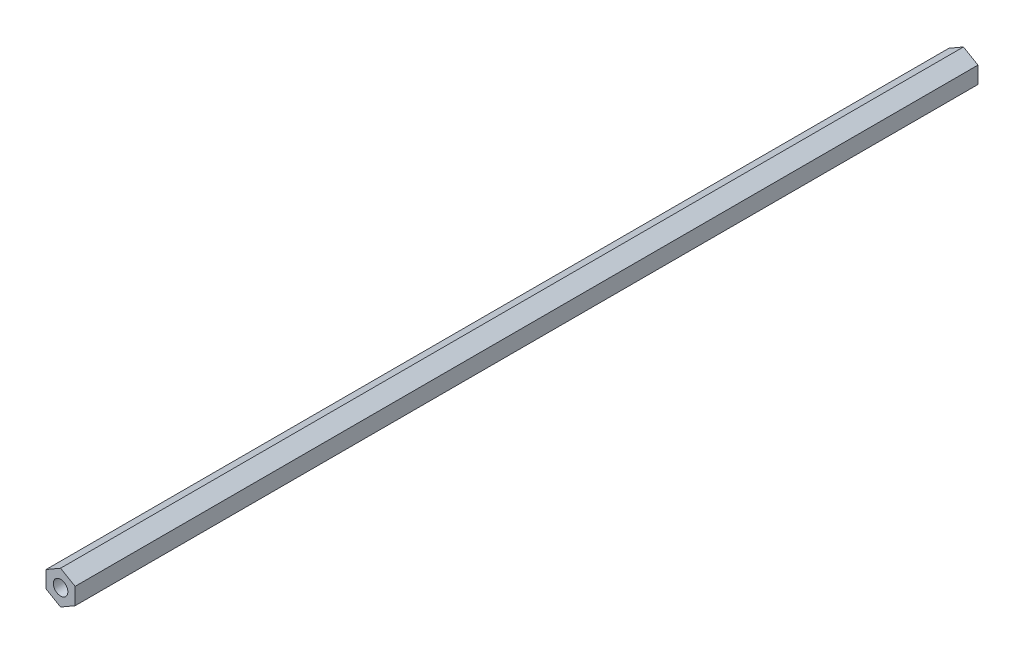
SolidWorks part; units mm, degrees
material "AISI 1020 Steel, Cold Rolled"
ref_plane "Front Plane" through (0, 0, 0) normal (0, 0, 1) x (1, 0, 0)
ref_plane "Top Plane" through (0, 0, 0) normal (0, 1, 0) x (1, 0, 0)
ref_plane "Right Plane" through (0, 0, 0) normal (1, 0, 0) x (0, 0, -1)
sketch "Sketch1" plane through (0, 0, 0) normal (0, 0, 1) x (1, 0, 0)
  line L1 (0, 7.3323) -> (-6.35, 3.6662) construction
  line L2 (-6.35, 3.6662) -> (-6.35, -3.6662) construction
  line L3 (-6.35, -3.6662) -> (0, -7.3323) construction
  line L4 (0, -7.3323) -> (6.35, -3.6662) construction
  line L5 (6.35, -3.6662) -> (6.35, 3.6662) construction
  line L6 (6.35, 3.6662) -> (0, 7.3323) construction
  circle A2 centre (0, 0) radius 6.35 construction
  dimension "Width" = 12.7
sketch "Sketch2" plane through (0, 0, 0) normal (1, 0, 0) x (0, 0, -1)
  line L0 (-196.85, 7.3323) -> (196.85, 7.3323) construction
  point P2 (0, 7.3323)
  point P3 (165.1, 7.3323)
  point P4 (-165.1, 7.3323)
  dimension "Length" = 393.7
  dimension "D2" = 31.75
  dimension "D1" = 31.75
sketch "Sketch3" plane through (0, 0, 0) normal (0, 0, 1) x (1, 0, 0)
  line L0 (-6.35, -3.6662) -> (0, -7.3323) construction
  line L1 (0, -7.3323) -> (6.35, -3.6662) construction
  line L2 (6.35, -3.6662) -> (6.35, 3.6662) construction
  line L3 (6.35, 3.6662) -> (0, 7.3323) construction
  line L4 (0, 7.3323) -> (-6.35, 3.6662) construction
  line L5 (-6.35, 3.6662) -> (-6.35, -3.6662) construction
  line L6 (-6.35, -3.6662) -> (0, -7.3323)
  line L7 (0, -7.3323) -> (6.35, -3.6662)
  line L8 (6.35, -3.6662) -> (6.35, 3.6662)
  line L9 (6.35, 3.6662) -> (0, 7.3323)
  line L10 (0, 7.3323) -> (-6.35, 3.6662)
  line L11 (-6.35, 3.6662) -> (-6.35, -3.6662)
extrude "Boss-Extrude2" add sketch "Sketch3" along normal up to vertex (196.85 mm away) and the other way up to vertex (196.85 mm away) up to point (0, 7.3323, 196.85) other way up to point (0, 7.3323, -196.85)
sketch "Sketch4" plane through (0, 0, 196.85) normal (0, 0, 1) x (1, 0, 0)
  point P0 (0, 0)
hole_wizard "1/4 (0.25) Diameter Hole1" positions "Sketch5" profile "Sketch6" hole size "1/4" standard "ANSI Inch"
sketch "Sketch5" plane through (0, 0, 196.85) normal (0, 0, 1) x (1, 0, 0)
  point P0 (0, 0)
sketch "Sketch6" plane through (0, 0, 196.85) normal (1, 0, 0) x (0, -1, 0)
  line L0 (0, 0) -> (0, 27.3077)
  line L1 (0, 27.3077) -> (3.175, 25.4)
  line L2 (3.175, 25.4) -> (3.175, 0)
  line L5 (3.175, 0) -> (0, 0)
  line L10 (0, 27.3077) -> (-3.175, 25.4) construction
  line L11 (0, -6.35) -> (0, 107.95) construction
  dimension "Hole Dia." = 6.35
  dimension "Hole Depth" = 25.4
  dimension "Drill Angle" = 118
hole_wizard "1/4 (0.25) Diameter Hole2" positions "Sketch7" profile "Sketch8" hole size "1/4" standard "ANSI Inch"
sketch "Sketch7" plane through (0, 0, -196.85) normal (0, 0, -1) x (-1, 0, 0)
  point P0 (0, 0)
sketch "Sketch8" plane through (0, 0, -196.85) normal (1, 0, 0) x (0, 1, 0)
  line L0 (0, 0) -> (0, 27.3077)
  line L1 (0, 27.3077) -> (3.175, 25.4)
  line L2 (3.175, 25.4) -> (3.175, 0)
  line L5 (3.175, 0) -> (0, 0)
  line L10 (0, 27.3077) -> (-3.175, 25.4) construction
  line L11 (0, -6.35) -> (0, 107.95) construction
  dimension "Hole Dia." = 6.35
  dimension "Hole Depth" = 25.4
  dimension "Drill Angle" = 118
equation "\"D2@Sketch2\" = \"D1@Sketch2\""
equation "\"D1@Sketch2\" = \"Width@Sketch1\" * 2.5"
